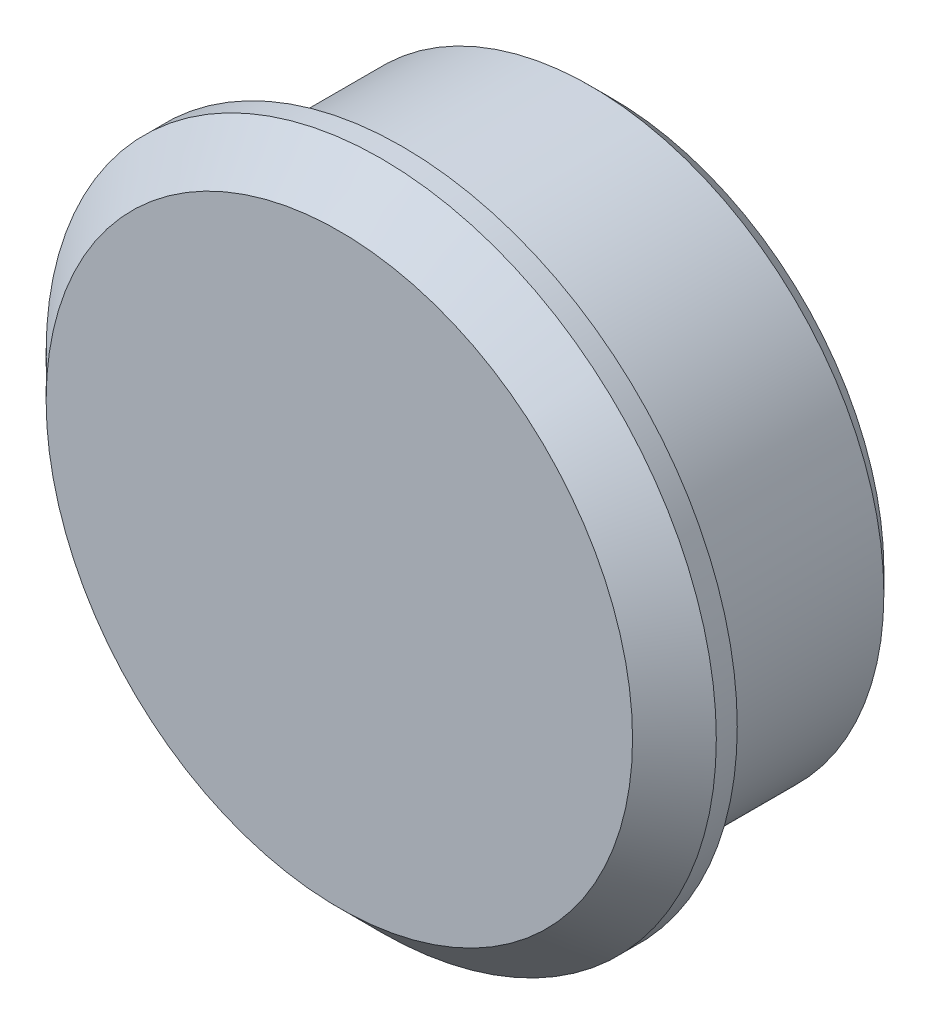
SolidWorks part; units mm, degrees
material "Oak"
ref_plane "Front Plane" through (0, 0, 0) normal (0, 0, 1) x (1, 0, 0)
ref_plane "Top Plane" through (0, 0, 0) normal (0, 1, 0) x (1, 0, 0)
ref_plane "Right Plane" through (0, 0, 0) normal (1, 0, 0) x (0, 0, -1)
sketch "Sketch1" plane through (0, 0, 0) normal (1, 0, 0) x (0, 0, -1)
  line L0 (0, 0) -> (42.5714, 0) construction
  line L1 (0, 0) -> (0, 14)
  line L3 (3, 16) -> (3, 14)
  line L4 (3, 14) -> (12, 14)
  line L5 (13, 13) -> (13, 11)
  line L6 (13, 11) -> (3, 11)
  line L7 (3, 11) -> (3, 0)
  line L8 (3, 0) -> (0, 0)
  line L9 (3, 16) -> (2, 16)
  line L10 (2, 16) -> (0, 14)
  line L11 (12, 14) -> (13, 13)
  point P7 (13, 14)
  dimension "D1" = 28
  dimension "D2" = 32
  dimension "D3" = 1
  dimension "D4" = 45
  dimension "D5" = 3
  dimension "D6" = 3
  dimension "D7" = 10
  dimension "D8" = 2
revolve "Revolve1" add sketch "Sketch1" angle 360 about L0
